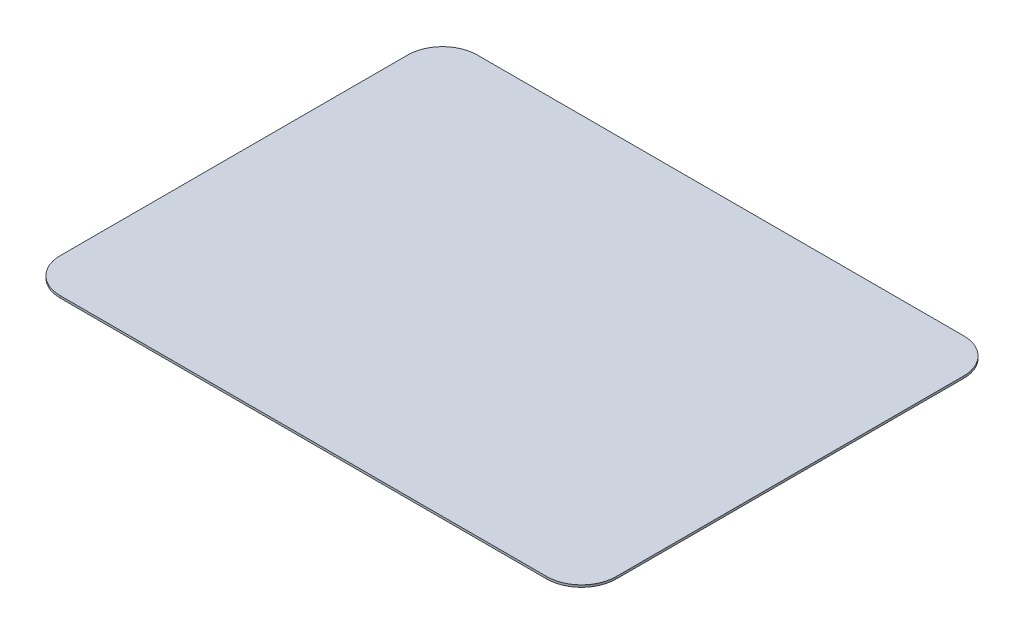
SolidWorks part; units mm, degrees
ref_plane "Front Plane" through (0, 0, 0) normal (0, 0, 1) x (1, 0, 0)
ref_plane "Top Plane" through (0, 0, 0) normal (0, 1, 0) x (1, 0, 0)
ref_plane "Right Plane" through (0, 0, 0) normal (1, 0, 0) x (0, 0, -1)
ref_plane "SheetPlane" through (0, 6.35, 0) normal (0, 1, 0) x (1, 0, 0)
sketch "Sketch1" plane through (0, 6.35, 0) normal (0, 1, 0) x (1, 0, 0)
  line L4 (101.6, -63.5) -> (101.6, 63.5)
  line L5 (88.9, 76.2) -> (-88.9, 76.2)
  line L6 (-101.6, 63.5) -> (-101.6, -63.5)
  line L7 (-88.9, -76.2) -> (88.9, -76.2)
  line L8 (101.6, -63.5) -> (101.6, 63.5)
  line L9 (88.9, 76.2) -> (-88.9, 76.2)
  line L10 (-101.6, 63.5) -> (-101.6, -63.5)
  line L11 (-88.9, -76.2) -> (88.9, -76.2)
  arc A4 (88.9, -76.2) -> (101.6, -63.5) centre (88.9, -63.5) ccw
  arc A5 (101.6, 63.5) -> (88.9, 76.2) centre (88.9, 63.5) ccw
  arc A6 (-88.9, 76.2) -> (-101.6, 63.5) centre (-88.9, 63.5) ccw
  arc A7 (-101.6, -63.5) -> (-88.9, -76.2) centre (-88.9, -63.5) ccw
  arc A8 (88.9, -76.2) -> (101.6, -63.5) centre (88.9, -63.5) ccw
  arc A9 (101.6, 63.5) -> (88.9, 76.2) centre (88.9, 63.5) ccw
  arc A10 (-88.9, 76.2) -> (-101.6, 63.5) centre (-88.9, 63.5) ccw
  arc A11 (-101.6, -63.5) -> (-88.9, -76.2) centre (-88.9, -63.5) ccw
  dimension "D1" = 0
extrude "MainBody" add sketch "Sketch1" along normal blind 0.7937
equation "\"SheetThickness\" = 0.03125in"
equation "\"D1@MainBody\" = \"SheetThickness\""
equation "\"SheetTolerance\"= 0.012in"
